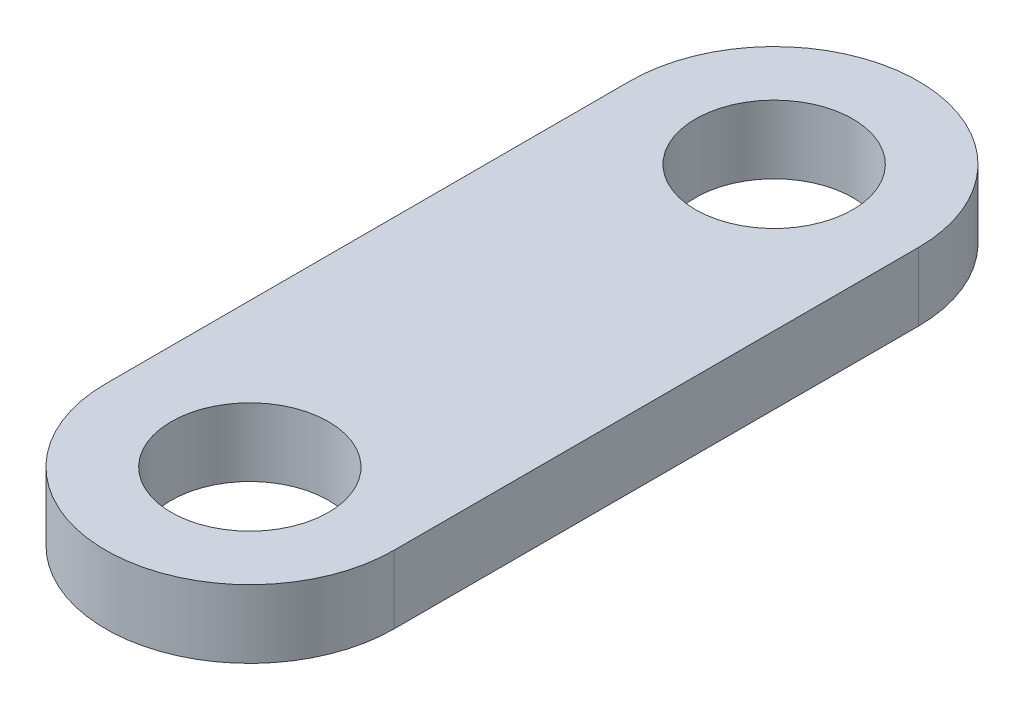
SolidWorks part; units mm, degrees
ref_plane "前视基准面" through (0, 0, 0) normal (0, 0, 1) x (1, 0, 0)
ref_plane "上视基准面" through (0, 0, 0) normal (0, 1, 0) x (1, 0, 0)
ref_plane "右视基准面" through (0, 0, 0) normal (1, 0, 0) x (0, 0, -1)
other "Configuration Table"
sketch "草图1" plane through (0, 0, 0) normal (0, 1, 0) x (1, 0, 0)
  line L0 (-10.1203, 0) -> (6.0958, 0) construction
  line L1 (0, 18.1035) -> (0, -7.6211) construction
  line L2 (0, 10) -> (0, -10) construction
  line L5 (5.5, 10) -> (5.5, -10)
  line L6 (-5.5, 10) -> (-5.5, -10)
  circle A2 centre (0, 10) radius 3
  circle A3 centre (0, -10) radius 3
  arc A4 (5.5, 10) -> (-5.5, 10) centre (0, 10) ccw
  arc A5 (-5.5, -10) -> (5.5, -10) centre (0, -10) ccw
  point P9 (0, 0)
  dimension "D1" = 6
  dimension "D3" = 5.5
  dimension "D2" = 20
extrude "凸台-拉伸1" add sketch "草图1" along normal blind 2.6
